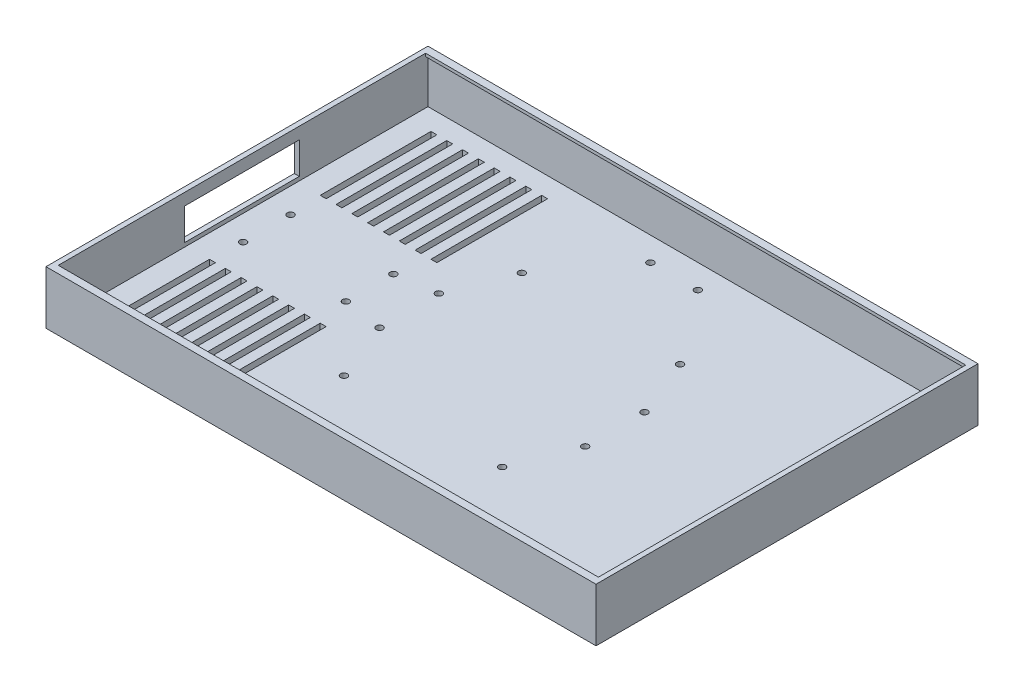
SolidWorks part; units mm, degrees
ref_plane "Front Plane" through (0, 0, 0) normal (0, 0, 1) x (1, 0, 0)
ref_plane "Top Plane" through (0, 0, 0) normal (0, 1, 0) x (1, 0, 0)
ref_plane "Right Plane" through (0, 0, 0) normal (1, 0, 0) x (0, 0, -1)
sketch "Sketch1" plane through (0, 0, 0) normal (0, 1, 0) x (1, 0, 0)
  line L1 (-139.1, -96.6) -> (139.1, -96.6)
  line L2 (-139.1, -96.6) -> (-139.1, 96.6)
  line L3 (-139.1, 96.6) -> (139.1, 96.6)
  line L4 (139.1, -96.6) -> (139.1, 96.6)
  line L5 (-139.1, -96.6) -> (139.1, 96.6) construction
  line L6 (-139.1, 96.6) -> (139.1, -96.6) construction
  dimension "D1" = 278.2
  dimension "D2" = 193.2
extrude "Shell Block" add sketch "Sketch1" along normal blind 27
ref_plane "Shell Front" through (0, 27, 0) normal (0, 1, 0) x (1, 0, 0)
sketch "Sketch2" plane through (0, 27, 0) normal (0, 1, 0) x (1, 0, 0)
  line L1 (-136.6, -92.9) -> (136.6, -92.9)
  line L2 (-136.6, -92.9) -> (-136.6, 92.9)
  line L3 (-136.6, 92.9) -> (136.6, 92.9)
  line L4 (136.6, -92.9) -> (136.6, 92.9)
  line L5 (-136.6, -92.9) -> (136.6, 92.9) construction
  line L6 (-136.6, 92.9) -> (136.6, -92.9) construction
  dimension "D1" = 273.2
  dimension "D2" = 185.8
extrude "Front Opening" cut sketch "Sketch2" against normal blind 1.5
ref_plane "Under Lip" through (0, 25.5, 0) normal (0, 1, 0) x (1, 0, 0)
sketch "Sketch3" plane through (0, 25.5, 0) normal (0, 1, 0) x (1, 0, 0)
  line L1 (-136.6, -94.1) -> (136.6, -94.1)
  line L2 (-136.6, -94.1) -> (-136.6, 94.1)
  line L3 (-136.6, 94.1) -> (136.6, 94.1)
  line L4 (136.6, -94.1) -> (136.6, 94.1)
  line L5 (-136.6, -94.1) -> (136.6, 94.1) construction
  line L6 (-136.6, 94.1) -> (136.6, -94.1) construction
  dimension "D1" = 273.2
  dimension "D2" = 188.2
extrude "Display Pocket" cut sketch "Sketch3" against normal blind 22.5
ref_plane "Back Inner" through (0, 3, 0) normal (0, 1, 0) x (1, 0, 0)
sketch "Sketch4" plane through (0, 3, 0) normal (0, 1, 0) x (1, 0, 0)
  line L1 (-69, 28) -> (-66, 28)
  line L2 (-69, 28) -> (-69, 84)
  line L3 (-69, 84) -> (-66, 84)
  line L4 (-66, 28) -> (-66, 84)
  line L6 (-69, -84) -> (-66, -84)
  line L7 (-69, -84) -> (-69, -28)
  line L8 (-69, -28) -> (-66, -28)
  line L9 (-66, -84) -> (-66, -28)
  line L11 (-77, 28) -> (-74, 28)
  line L12 (-77, 28) -> (-77, 84)
  line L13 (-77, 84) -> (-74, 84)
  line L14 (-74, 28) -> (-74, 84)
  line L16 (-77, -84) -> (-74, -84)
  line L17 (-77, -84) -> (-77, -28)
  line L18 (-77, -28) -> (-74, -28)
  line L19 (-74, -84) -> (-74, -28)
  line L21 (-85, 28) -> (-82, 28)
  line L22 (-85, 28) -> (-85, 84)
  line L23 (-85, 84) -> (-82, 84)
  line L24 (-82, 28) -> (-82, 84)
  line L26 (-85, -84) -> (-82, -84)
  line L27 (-85, -84) -> (-85, -28)
  line L28 (-85, -28) -> (-82, -28)
  line L29 (-82, -84) -> (-82, -28)
  line L31 (-93, 28) -> (-90, 28)
  line L32 (-93, 28) -> (-93, 84)
  line L33 (-93, 84) -> (-90, 84)
  line L34 (-90, 28) -> (-90, 84)
  line L36 (-93, -84) -> (-90, -84)
  line L37 (-93, -84) -> (-93, -28)
  line L38 (-93, -28) -> (-90, -28)
  line L39 (-90, -84) -> (-90, -28)
  line L41 (-101, 28) -> (-98, 28)
  line L42 (-101, 28) -> (-101, 84)
  line L43 (-101, 84) -> (-98, 84)
  line L44 (-98, 28) -> (-98, 84)
  line L46 (-101, -84) -> (-98, -84)
  line L47 (-101, -84) -> (-101, -28)
  line L48 (-101, -28) -> (-98, -28)
  line L49 (-98, -84) -> (-98, -28)
  line L51 (-109, 28) -> (-106, 28)
  line L52 (-109, 28) -> (-109, 84)
  line L53 (-109, 84) -> (-106, 84)
  line L54 (-106, 28) -> (-106, 84)
  line L56 (-109, -84) -> (-106, -84)
  line L57 (-109, -84) -> (-109, -28)
  line L58 (-109, -28) -> (-106, -28)
  line L59 (-106, -84) -> (-106, -28)
  line L61 (-117, 28) -> (-114, 28)
  line L62 (-117, 28) -> (-117, 84)
  line L63 (-117, 84) -> (-114, 84)
  line L64 (-114, 28) -> (-114, 84)
  line L66 (-117, -84) -> (-114, -84)
  line L67 (-117, -84) -> (-117, -28)
  line L68 (-117, -28) -> (-114, -28)
  line L69 (-114, -84) -> (-114, -28)
  line L71 (-125, 28) -> (-122, 28)
  line L72 (-125, 28) -> (-125, 84)
  line L73 (-125, 84) -> (-122, 84)
  line L74 (-122, 28) -> (-122, 84)
  line L76 (-125, -84) -> (-122, -84)
  line L77 (-125, -84) -> (-125, -28)
  line L78 (-125, -28) -> (-122, -28)
  line L79 (-122, -84) -> (-122, -28)
extrude "Vent Slots" cut sketch "Sketch4" against normal blind 4
sketch "Sketch5" plane through (0, 0, 0) normal (1, 0, 0) x (0, 0, -1)
  line L1 (-29, 5) -> (29, 5)
  line L2 (-29, 5) -> (-29, 21)
  line L3 (-29, 21) -> (29, 21)
  line L4 (29, 5) -> (29, 21)
extrude "Cable Exit (-X short side)" cut sketch "Sketch5" against normal blind 140.1
sketch "Sketch6" plane through (0, 3, 0) normal (0, 1, 0) x (1, 0, 0)
  circle A0 centre (-40, -45) radius 1.7
  circle A1 centre (-40, 45) radius 1.7
  circle A2 centre (40, -45) radius 1.7
  circle A3 centre (40, 45) radius 1.7
  circle A4 centre (-52, -15) radius 1.7
  circle A5 centre (-52, 15) radius 1.7
  circle A6 centre (52, -15) radius 1.7
  circle A7 centre (52, 15) radius 1.7
  circle A8 centre (-12, -82) radius 1.7
  circle A9 centre (-12, 82) radius 1.7
  circle A10 centre (12, -82) radius 1.7
  circle A11 centre (12, 82) radius 1.7
  circle A12 centre (-124, -12) radius 1.7
  circle A13 centre (-124, 12) radius 1.7
  circle A14 centre (124, -12) radius 1.7
  circle A15 centre (124, 12) radius 1.7
  circle A16 centre (-72, 12) radius 1.7
  circle A17 centre (-72, -12) radius 1.7
extrude "Bolt Holes" cut sketch "Sketch6" against normal blind 4
equation "\"DispL\" = 272.0"
equation "\"DispW\" = 187.0"
equation "\"DispT\" = 20.0"
equation "\"Clr\" = 0.6"
equation "\"Wall\" = 2.5"
equation "\"BackT\" = 3.0"
equation "\"CableRoom\" = 4.0"
equation "\"LipW\" = 1.2"
equation "\"LipT\" = 1.5"
equation "\"CableW\" = 58.0"
equation "\"CableH\" = 16.0"
equation "\"BoltD\" = 3.4"
equation "\"ShellL\" = \"DispL\" + 2 * \"Clr\" + 2 * \"Wall\""
equation "\"ShellW\" = \"DispW\" + 2 * \"Clr\" + 2 * \"Wall\""
equation "\"ShellH\" = \"BackT\" + \"DispT\" + \"CableRoom\""
equation "\"D1@Sketch1\" = \"ShellL\""
equation "\"D2@Sketch1\" = \"ShellW\""
equation "\"D1@Shell Block\" = \"ShellH\""
equation "\"D1@Shell Front\" = \"ShellH\""
equation "\"D1@Sketch2\" = \"DispL\" + 2 * \"Clr\""
equation "\"D2@Sketch2\" = \"DispW\" + 2 * \"Clr\" - 2 * \"LipW\""
equation "\"D1@Front Opening\" = \"LipT\""
equation "\"D1@Under Lip\" = \"ShellH\" - \"LipT\""
equation "\"D1@Sketch3\" = \"DispL\" + 2 * \"Clr\""
equation "\"D2@Sketch3\" = \"DispW\" + 2 * \"Clr\""
equation "\"D1@Display Pocket\" = \"ShellH\" - \"LipT\" - \"BackT\""
equation "\"D1@Back Inner\" = \"BackT\""
